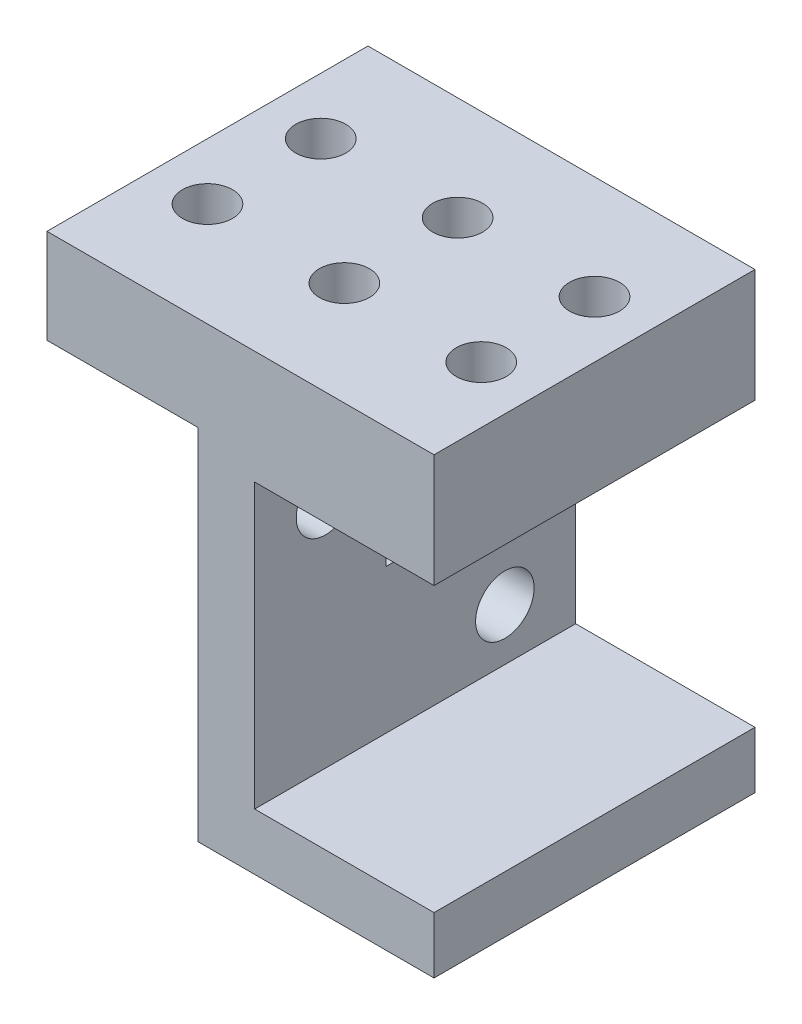
SolidWorks part; units mm, degrees
material "Aluminum"
ref_plane "Front Plane" through (0, 0, 0) normal (0, 0, 1) x (1, 0, 0)
ref_plane "Top Plane" through (0, 0, 0) normal (0, 1, 0) x (1, 0, 0)
ref_plane "Right Plane" through (0, 0, 0) normal (1, 0, 0) x (0, 0, -1)
sketch "Sketch1" plane through (0, 0, 0) normal (0, 0, 1) x (1, 0, 0)
  line L1 (0, 0) -> (5, 0)
  line L2 (0, 0) -> (0, 24)
  line L3 (0, 24) -> (5, 24)
  line L4 (3, 3) -> (3, 18)
  line L5 (0, 0) -> (12.5, 0)
  line L6 (0, 0) -> (0, 2.9889)
  line L7 (3, 3) -> (12.5, 3)
  line L8 (12.5, 0) -> (12.5, 3)
  line L9 (0, 24) -> (12.5, 24)
  line L10 (0, 24) -> (0, 17.9889)
  line L11 (3, 18) -> (12.5, 18)
  line L12 (12.5, 24) -> (12.5, 18)
  dimension "D1" = 15
  dimension "D2" = 9.5
  dimension "D3" = 9.5
  dimension "D4" = 3
  dimension "D5" = 3
  dimension "D6" = 6
extrude "Boss-Extrude1" add sketch "Sketch1" along normal blind 17 contours L12 L9 L3 L2 L1 L5 L8 L7 L4 L11
hole_wizard "Ø3.0 (3) Diameter Hole1" positions "Sketch3" profile "Sketch2" hole size "Ø3.0" standard "ISO" end condition through all
sketch "Sketch3" plane through (3, 0, 0) normal (1, 0, 0) x (0, 0, -1)
  point P0 (-13.25, 15.25)
  point P2 (-3.75, 5.75)
sketch "Sketch2" plane through (3, 15.25, 13.25) normal (0, 1, 0) x (0, 0, -1)
  line L0 (0, 0) -> (0, 3)
  line L1 (0, 3) -> (1.55, 3)
  line L2 (1.55, 3) -> (1.55, 0)
  line L5 (1.55, 0) -> (0, 0)
  line L11 (0, -6.35) -> (0, 107.95) construction
  dimension "Thru Hole Dia." = 3.1
  dimension "Thru Hole Depth" = 3
hole_wizard "Tap Drill for M2.5 Tap1" positions "Sketch7" profile "Sketch6" hole size "M2.5" standard "ISO"
sketch "Sketch7" plane through (0, 24, 0) normal (0, 1, 0) x (1, 0, 0)
  line L0 (0, -17) -> (0, 0) construction
  line L2 (0, 0) -> (12.5, 0) construction
  line L3 (12.5, -17) -> (12.5, 0) construction
  line L4 (0, -17) -> (12.5, -17) construction
  point P0 (2.25, -5.5)
  point P2 (2.25, -11.5)
  point P4 (9.5, -11.5)
  point P18 (9.5, -5.5)
  dimension "2" = 2.25
  dimension "D2" = 2.25
  dimension "D3" = 3
  dimension "D4" = 5.5
  dimension "D5" = 5.5
  dimension "D6" = 5.5
  dimension "D7" = 3
  dimension "D8" = 5.5
sketch "Sketch6" plane through (2.25, 24, 5.5) normal (1, 0, 0) x (0, 0, 1)
  line L0 (0, 0) -> (0, 4.3)
  line L1 (0, 4.3) -> (1.325, 4.3)
  line L2 (1.325, 4.3) -> (1.325, 0)
  line L5 (1.325, 0) -> (0, 0)
  line L10 (0, 4.3) -> (-1.325, 4.3) construction
  line L11 (0, -6.35) -> (0, 107.95) construction
  dimension "Hole Dia." = 2.65
  dimension "Hole Depth" = 4.3
  dimension "Drill Angle" = 180
sketch "Sketch8" plane through (3, 0, 0) normal (1, 0, 0) x (0, 0, -1)
  line L0 (-17, 18) -> (0, 18) construction
  line L1 (-10.05, 17.15) -> (-0.85, 17.15)
  line L2 (-10.05, 17.15) -> (-10.05, 10.65)
  line L3 (-10.05, 10.65) -> (-0.85, 10.65)
  line L4 (-0.85, 17.15) -> (-0.85, 10.65)
  line L5 (0, 3) -> (0, 18) construction
  dimension "D1" = 9.2
  dimension "D2" = 6.5
  dimension "D3" = 0.85
  dimension "D4" = 0.85
extrude "Cut-Extrude1" cut sketch "Sketch8" against normal blind 10
sketch "Sketch9" plane through (0, 0, 17) normal (0, 0, 1) x (1, 0, 0)
  line L1 (0, 24) -> (-8, 24)
  line L2 (0, 24) -> (0, 18)
  line L3 (0, 18) -> (-8, 18)
  line L4 (-8, 24) -> (-8, 18)
  dimension "D1" = 6
  dimension "D2" = 8
extrude "Boss-Extrude2" add sketch "Sketch9" against normal blind 17
hole_wizard "Tap Drill for M2.5 Tap2" positions "Sketch11" profile "Sketch10" hole size "M2.5" standard "ISO"
sketch "Sketch11" plane through (0, 24, 0) normal (0, 1, 0) x (1, 0, 0)
  line L0 (-8, -17) -> (12.5, -17) construction
  line L1 (-8, 0) -> (12.5, 0) construction
  line L2 (-8, 0) -> (-8, -17) construction
  point P0 (-5, -11.5)
  point P2 (-5, -5.5)
  dimension "D1" = 5.5
  dimension "D2" = 5.5
  dimension "D3" = 3
  dimension "D4" = 3
sketch "Sketch10" plane through (-5, 24, 11.5) normal (1, 0, 0) x (0, 0, 1)
  line L0 (0, 0) -> (0, 4.3)
  line L1 (0, 4.3) -> (1.325, 4.3)
  line L2 (1.325, 4.3) -> (1.325, 0)
  line L5 (1.325, 0) -> (0, 0)
  line L10 (0, 4.3) -> (-1.325, 4.3) construction
  line L11 (0, -6.35) -> (0, 107.95) construction
  dimension "Hole Dia." = 2.65
  dimension "Hole Depth" = 4.3
  dimension "Drill Angle" = 180
sketch "Sketch12" plane through (0, 0, 17) normal (0, 0, 1) x (1, 0, 0)
  line L1 (-8, 18) -> (0, 18)
  line L2 (-8, 18) -> (-8, 19)
  line L3 (-8, 19) -> (0, 19)
  line L4 (0, 18) -> (0, 19)
  dimension "D1" = 8
  dimension "D2" = 1
extrude "Cut-Extrude2" cut sketch "Sketch12" against normal blind 26
